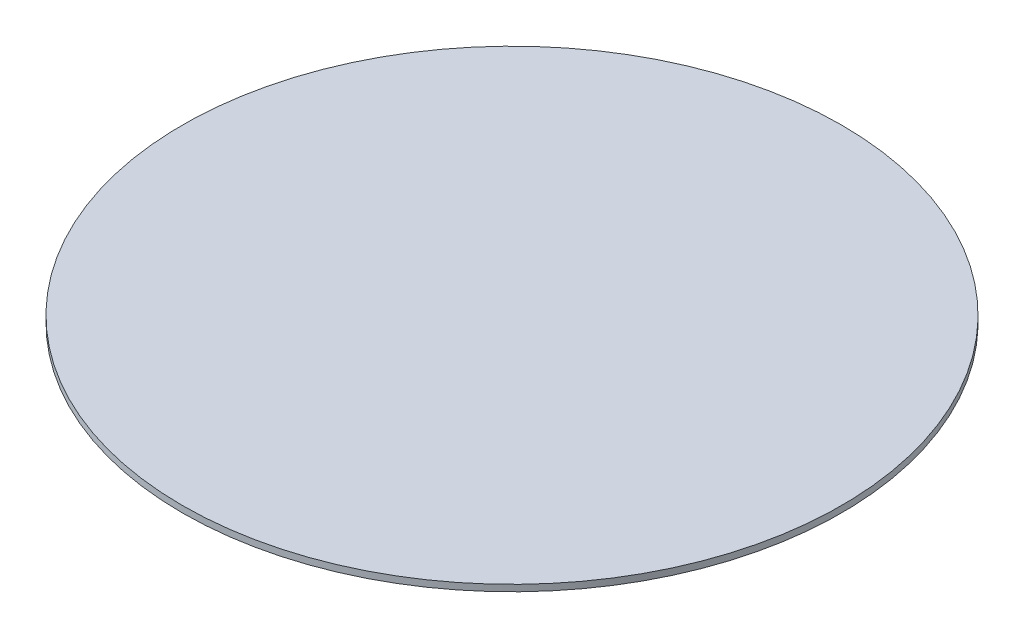
SolidWorks part; units mm, degrees
ref_plane "Front" through (0, 0, 0) normal (0, 0, 1) x (1, 0, 0)
ref_plane "Top" through (0, 0, 0) normal (0, 1, 0) x (1, 0, 0)
ref_plane "Right" through (0, 0, 0) normal (1, 0, 0) x (0, 0, -1)
sketch "Sketch1" plane through (0, 0, 0) normal (0, 1, 0) x (1, 0, 0)
  circle A0 centre (0, 0) radius 161.5
  dimension "D1" = 323
extrude "Boss-Extrude1" add sketch "Sketch1" along normal blind 3.175
